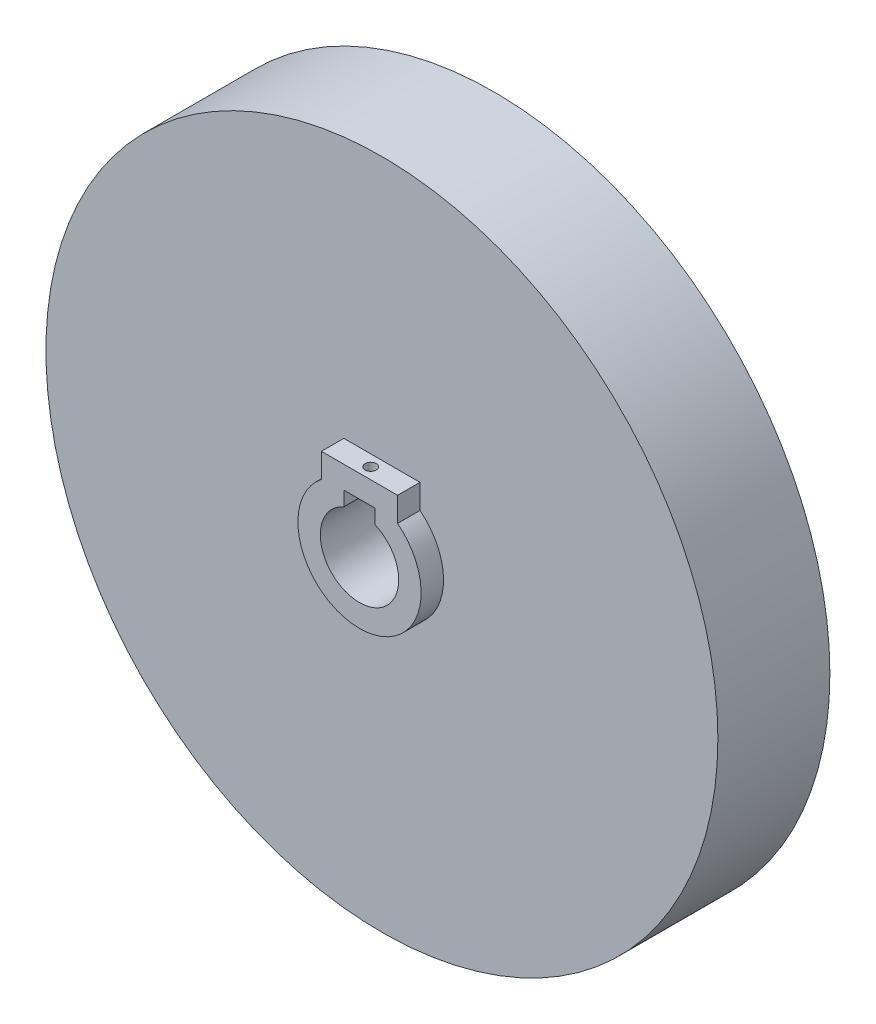
SolidWorks part; units mm, degrees
ref_plane "Front" through (0, 0, 0) normal (0, 0, 1) x (1, 0, 0)
ref_plane "Top" through (0, 0, 0) normal (0, 1, 0) x (1, 0, 0)
ref_plane "Right" through (0, 0, 0) normal (1, 0, 0) x (0, 0, -1)
sketch "Sketch1" plane through (0, 0, 0) normal (0, 0, 1) x (1, 0, 0)
  line L2 (-7, 22.5) -> (7, 22.5)
  line L3 (-7, 22.5) -> (-7, 16.039)
  line L5 (7, 22.5) -> (7, 16.039)
  circle A0 centre (0, 0) radius 150
  arc A1 (-7, 16.039) -> (7, 16.039) centre (0, 0) ccw
  dimension "D1" = 300
  dimension "D2" = 35
  dimension "D4" = 14
extrude "Boss-Extrude1" add sketch "Sketch1" along normal blind 50
sketch "Sketch2" plane through (0, 0, 50) normal (0, 0, 1) x (1, 0, 0)
  line L0 (7, 16.039) -> (7, 22.5) construction
  line L1 (7, 22.5) -> (-7, 22.5) construction
  line L2 (-7, 22.5) -> (-7, 16.039) construction
  line L3 (7, 16.039) -> (7, 22.5)
  line L4 (7, 22.5) -> (-7, 22.5)
  line L5 (-7, 22.5) -> (-7, 16.039)
  line L6 (17, 21.616) -> (17, 32.5)
  line L7 (17, 32.5) -> (-17, 32.5)
  line L8 (-17, 32.5) -> (-17, 21.616)
  arc A0 (-7, 16.039) -> (7, 16.039) centre (0, 0) ccw construction
  arc A1 (-7, 16.039) -> (7, 16.039) centre (0, 0) ccw
  arc A2 (-17, 21.616) -> (17, 21.616) centre (0, 0) ccw
  dimension "D1" = 10
extrude "Boss-Extrude2" add sketch "Sketch2" along normal blind 10 and the other way blind 60
sketch "Sketch3" plane through (0, 32.5, 0) normal (0, 1, 0) x (1, 0, 0)
  line L0 (0, -60) -> (0, -55) construction
  line L1 (17, -60) -> (-17, -60) construction
  circle A0 centre (0, -55) radius 2.5
  dimension "D2" = 5
  dimension "D1" = 5
extrude "Cut-Extrude1" cut sketch "Sketch3" against normal blind 10
